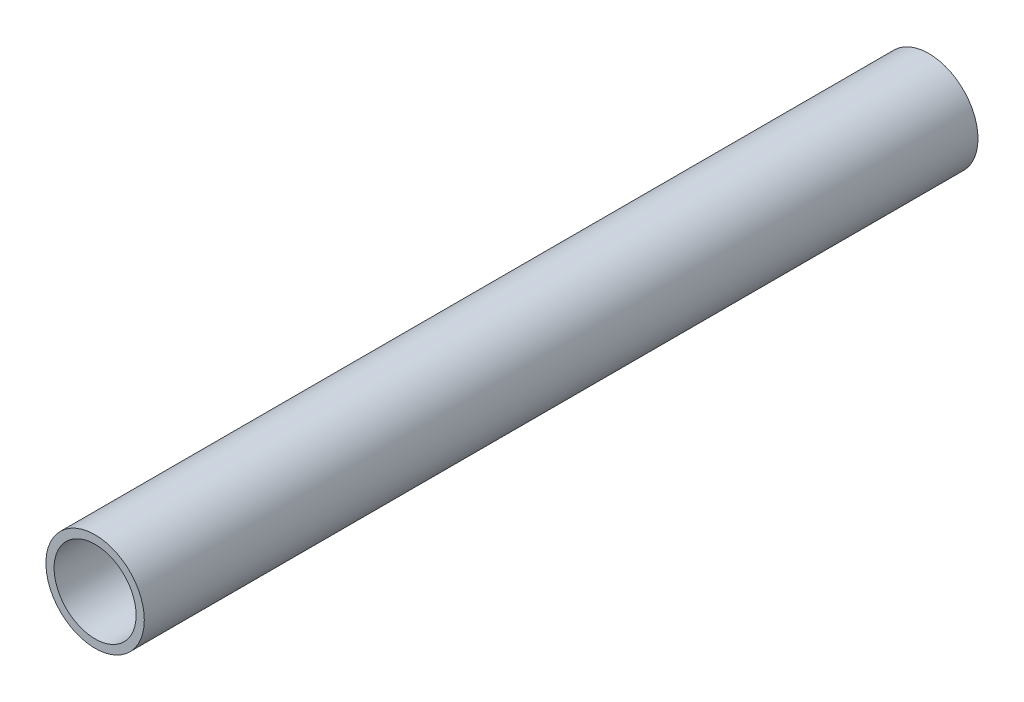
SolidWorks part; units mm, degrees
ref_plane "Plan de face" through (0, 0, 0) normal (0, 0, 1) x (1, 0, 0)
ref_plane "Plan de dessus" through (0, 0, 0) normal (0, 1, 0) x (1, 0, 0)
ref_plane "Plan de droite" through (0, 0, 0) normal (1, 0, 0) x (0, 0, -1)
sketch "Esquisse1" plane through (0, 0, 0) normal (0, 0, 1) x (1, 0, 0)
  circle A0 centre (0, 0) radius 15
extrude "Extru.-Mince1" add sketch "Esquisse1" along normal blind 305 thin
